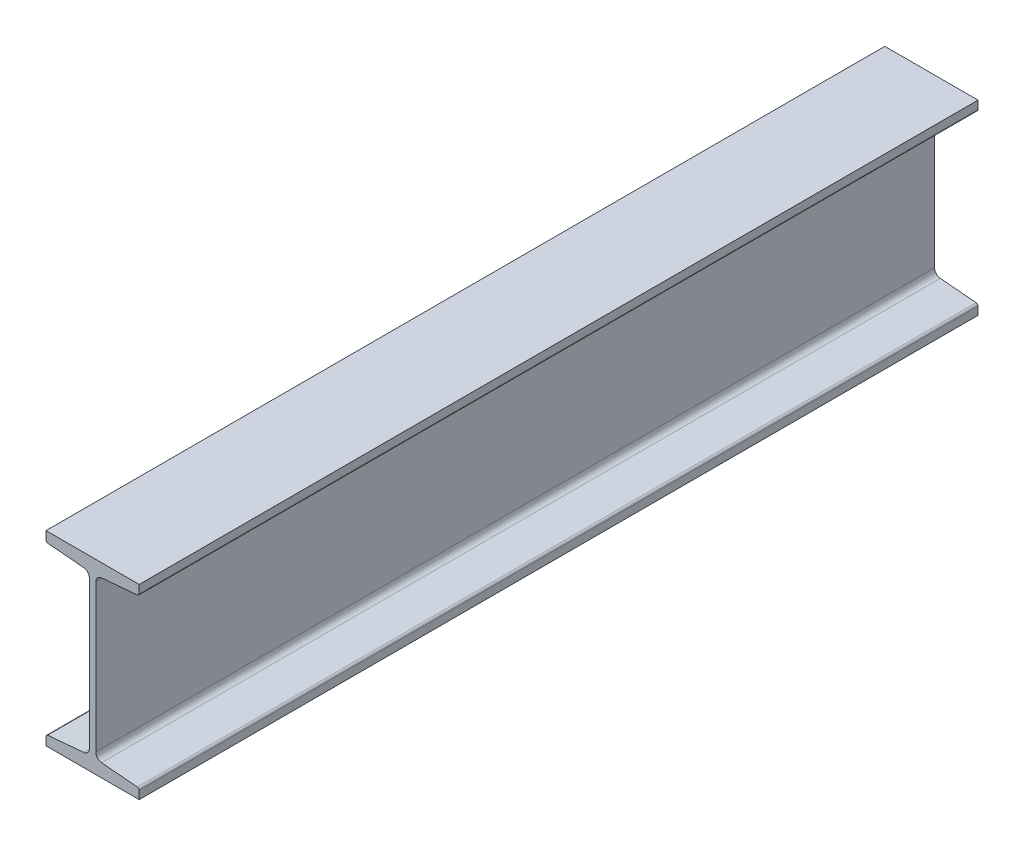
SolidWorks part; units mm, degrees
ref_plane "Front Plane" through (0, 0, 0) normal (0, 0, 1) x (1, 0, 0)
ref_plane "Top Plane" through (0, 0, 0) normal (0, 1, 0) x (1, 0, 0)
ref_plane "Right Plane" through (0, 0, 0) normal (1, 0, 0) x (0, 0, -1)
sketch "Sketch1" plane through (0, 0, 0) normal (0, 0, 1) x (1, 0, 0)
  line L0 (0, -101.6) -> (0, 101.6) construction
  line L1 (-3.4417, 0) -> (3.4417, 0) construction
  line L2 (-50.8, 101.6) -> (50.8, 101.6)
  line L3 (-50.8, -101.6) -> (50.8, -101.6)
  line L4 (50.8, -101.6) -> (50.8, -90.805)
  line L5 (-3.4417, 101.6) -> (-3.4417, -101.6) construction
  line L6 (3.4417, -101.6) -> (3.4417, 101.6) construction
  point P4 (0, 0)
  point P8 (0, 0)
  point P11 (0, 101.6)
  point P14 (0, -101.6)
  dimension "Outside Width" = 101.6
  dimension "Outside Height" = 203.2
  dimension "Wall Thickness" = 10.795
  dimension "C Thickness of Web" = 6.8834
sketch "Sketch2" plane through (0, 0, 0) normal (1, 0, 0) x (0, 0, -1)
  line L1 (-457.2, 101.6) -> (457.2, 101.6)
  line L2 (-457.2, 101.6) -> (-457.2, -101.6)
  line L3 (-457.2, -101.6) -> (457.2, -101.6)
  line L4 (457.2, 101.6) -> (457.2, -101.6)
  point P4 (274.32, 101.6)
  point P7 (-274.32, 101.6)
  dimension "Length" = 914.4
  dimension "D1" = 182.88
  dimension "D2" = 182.88
sketch "Sketch3" plane through (0, 0, 0) normal (0, 0, 1) x (1, 0, 0)
  line L0 (-50.8, -101.6) -> (50.8, -101.6)
  line L1 (50.8, -101.6) -> (50.8, -92.7834)
  line L2 (50.8, -101.6) -> (50.8, -90.805) construction
  line L4 (48.8292, -90.6326) -> (9.7252, -87.2114)
  line L5 (3.4417, -101.6) -> (3.4417, 101.6) construction
  line L6 (3.4417, -80.3542) -> (10.3251, -80.3542) construction
  line L7 (3.4417, -80.3542) -> (-3.4417, -80.3542) construction
  line L8 (-3.4417, 101.6) -> (-3.4417, -101.6) construction
  line L9 (0, -101.6) -> (0, 101.6) construction
  line L10 (-3.4417, 0) -> (3.4417, 0) construction
  line L11 (0, -101.6) -> (0, 101.6) construction
  line L12 (-3.4417, 0) -> (3.4417, 0) construction
  line L13 (-48.8292, -90.6326) -> (-9.7252, -87.2114)
  line L14 (-50.8, -101.6) -> (-50.8, -92.7834)
  line L15 (50.8, 101.6) -> (50.8, 92.7834)
  line L16 (48.8292, 90.6326) -> (9.7252, 87.2114)
  line L17 (-48.8292, 90.6326) -> (-9.7252, 87.2114)
  line L18 (-50.8, 101.6) -> (-50.8, 92.7834)
  line L19 (-50.8, 101.6) -> (50.8, 101.6)
  line L20 (-3.4417, 80.3542) -> (-3.4417, -80.3542)
  line L21 (3.4417, 80.3542) -> (3.4417, -80.3542)
  arc A0 (50.8, -92.7834) -> (48.8292, -90.6326) centre (48.641, -92.7834) ccw
  arc A1 (9.7252, -87.2114) -> (3.4417, -80.3542) centre (10.3251, -80.3542) cw
  arc A2 (-9.7252, -87.2114) -> (-3.4417, -80.3542) centre (-10.3251, -80.3542) ccw
  arc A3 (-50.8, -92.7834) -> (-48.8292, -90.6326) centre (-48.641, -92.7834) cw
  arc A4 (50.8, 92.7834) -> (48.8292, 90.6326) centre (48.641, 92.7834) cw
  arc A5 (9.7252, 87.2114) -> (3.4417, 80.3542) centre (10.3251, 80.3542) ccw
  arc A6 (-9.7252, 87.2114) -> (-3.4417, 80.3542) centre (-10.3251, 80.3542) cw
  arc A7 (-50.8, 92.7834) -> (-48.8292, 90.6326) centre (-48.641, 92.7834) ccw
  dimension "D2" = 2.159
  dimension "D1" = 5
extrude "Boss-Extrude1" add sketch "Sketch3" along normal up to vertex (457.2 mm away) from vertex at -457.2 starting at point (0, 101.6, -457.2)
equation "\"D1@Sketch2\" = IIF ( \"Outside Height@Sketch1\" / \"Outside Width@Sketch1\" > 2.25 , \"Outside Width@Sketch1\" , \"Outside Height@Sketch1\" * .9 )"
equation "\"D2@Sketch2\"=\"D1@Sketch2\""
equation "\"D2@Sketch3\"= \"Wall Thickness@Sketch1\" * .2"
